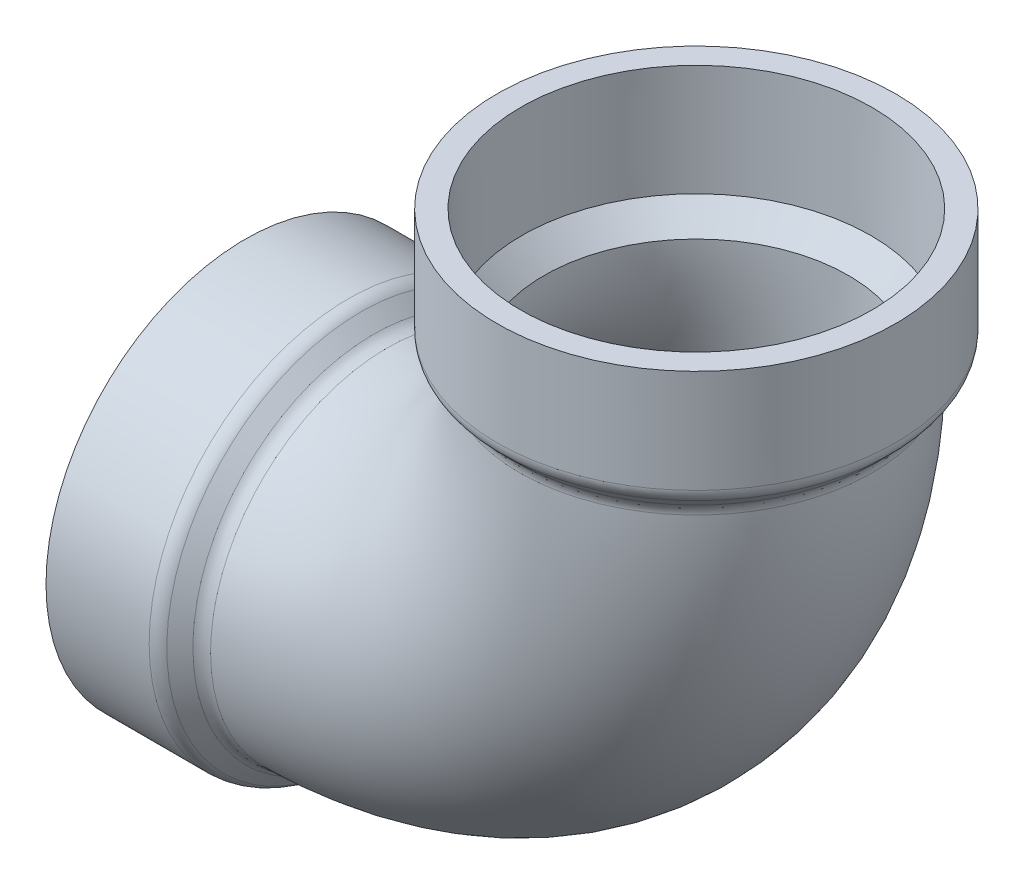
SolidWorks part; units mm, degrees
material "ABS"
ref_plane "Front Plane" through (0, 0, 0) normal (0, 0, 1) x (1, 0, 0)
ref_plane "Top Plane" through (0, 0, 0) normal (0, 1, 0) x (1, 0, 0)
ref_plane "Right Plane" through (0, 0, 0) normal (1, 0, 0) x (0, 0, -1)
sketch "Sketch0" plane through (0, 0, 0) normal (0, 0, 1) x (1, 0, 0)
  line L0 (-77.7875, 0) -> (0, 0) construction
  line L1 (0, 0) -> (0, 77.7875) construction
  line L2 (-58.7375, 0) -> (0, 0) construction
  line L3 (0, 0) -> (0, 58.7375) construction
  line L4 (-77.7875, 34.3535) -> (-77.7875, -34.3535) construction
  line L5 (-58.7375, 30.099) -> (-77.7875, 30.2895) construction
  line L6 (-58.7375, 30.099) -> (-58.7375, -30.099) construction
  line L7 (-58.7375, -30.099) -> (-77.7875, -30.2895) construction
  line L8 (-77.7875, 30.2895) -> (-77.7875, -30.2895) construction
  line L9 (-34.3535, 77.7875) -> (34.3535, 77.7875) construction
  line L10 (-30.2895, 77.7875) -> (30.2895, 77.7875) construction
  line L11 (30.2895, 77.7875) -> (30.099, 58.7375) construction
  line L12 (30.099, 58.7375) -> (-30.099, 58.7375) construction
  line L13 (-30.099, 58.7375) -> (-30.2895, 77.7875) construction
  line L14 (-58.7375, 26.2509) -> (-58.7375, -26.2509) construction
  line L15 (-58.7375, -26.2509) -> (-58.7375, -30.3149) construction
  line L16 (-77.7875, -30.2895) -> (-77.7875, -34.3535) construction
  line L17 (26.2509, 58.7375) -> (30.3149, 58.7375) construction
  line L18 (-26.2509, 58.7375) -> (26.2509, 58.7375) construction
  line L19 (30.2895, 77.7875) -> (34.3535, 77.7875) construction
  line L20 (0, 77.7875) -> (0, 58.7375) construction
  line L21 (-77.7875, 0) -> (-58.7375, 0) construction
sketch "Sketch1" plane through (0, 0, 0) normal (0, 0, 1) x (1, 0, 0)
  line L0 (-77.7875, 0) -> (0, 0) construction
  line L1 (-77.7875, 0) -> (0, 0) construction
  line L2 (-58.7375, -34.3535) -> (-54.6989, -30.3149)
  line L3 (-77.7875, -34.3535) -> (-58.7375, -34.3535)
  line L4 (-77.7875, -34.3535) -> (-77.7875, -30.2895)
  line L5 (-77.7875, -30.2895) -> (-58.7375, -30.099)
  line L6 (-58.7375, -34.3535) -> (-58.7375, -30.099) construction
  line L7 (-54.6989, -30.3149) -> (-54.6989, -26.2509)
  line L8 (-54.6989, -26.2509) -> (-58.7375, -30.099)
  line L9 (-58.7375, -34.3535) -> (-54.6989, -34.3535) construction
  line L10 (-58.7375, -26.2509) -> (-54.6989, -26.2509) construction
  line L11 (-54.6989, -34.3535) -> (-54.6989, -30.3149) construction
  line L12 (-58.7375, -30.3149) -> (-54.6989, -30.3149) construction
revolve "Revolve1" add sketch "Sketch1" angle 360 about L1
sketch "Sketch2" plane through (0, 0, 0) normal (0, 0, 1) x (1, 0, 0)
  line L0 (30.2895, 77.7875) -> (30.099, 58.7375)
  line L1 (30.099, 58.7375) -> (34.3535, 58.7375) construction
  line L2 (34.3535, 58.7375) -> (34.3535, 77.7875)
  line L3 (34.3535, 77.7875) -> (30.2895, 77.7875)
  line L4 (0, 0) -> (0, 77.7875) construction
  line L5 (0, 0) -> (0, 77.7875) construction
  line L6 (30.099, 58.7375) -> (26.2509, 54.6989)
  line L7 (26.2509, 58.7375) -> (26.2509, 54.6989) construction
  line L8 (34.3535, 58.7375) -> (30.3149, 54.6989)
  line L9 (30.3149, 54.6989) -> (26.2509, 54.6989)
  line L10 (34.3535, 58.7375) -> (34.3535, 54.6989) construction
  line L11 (34.3535, 54.6989) -> (30.3149, 54.6989) construction
  line L12 (30.3149, 58.7375) -> (30.3149, 54.6989) construction
revolve "Revolve2" add sketch "Sketch2" angle 360 about L5
sketch "Sketch3" plane through (-54.6989, 0, 0) normal (1, 0, 0) x (0, 0, -1)
  circle A0 centre (0, 0) radius 26.2509
  circle A1 centre (0, 0) radius 30.3149
sketch "Sketch4" plane through (0, 0, 0) normal (0, 0, 1) x (1, 0, 0)
  line L0 (-77.7875, 0) -> (0, 0) construction
  line L1 (0, 0) -> (0, 77.7875) construction
  line L2 (-77.7875, 0) -> (-54.6989, 0) construction
  line L3 (0, 54.6989) -> (0, 77.7875) construction
  line L4 (-54.6989, -30.3149) -> (-54.6989, 30.3149) construction
  arc A0 (-54.6989, 0) -> (0, 54.6989) centre (-54.6989, 54.6989) ccw
sweep "Sweep1" add profiles "Sketch3" path "Sketch4"
fillet "Fillet1" radius 3.048 4 edges at (-54.6989, 0, -30.3149) (0, 54.6989, -30.3149) (0, 58.7375, -34.3535) (-58.7375, 0, 34.3535)
equation "\"D1@Fillet1\" = \"H@Sketch0\" * 3 / 4"
